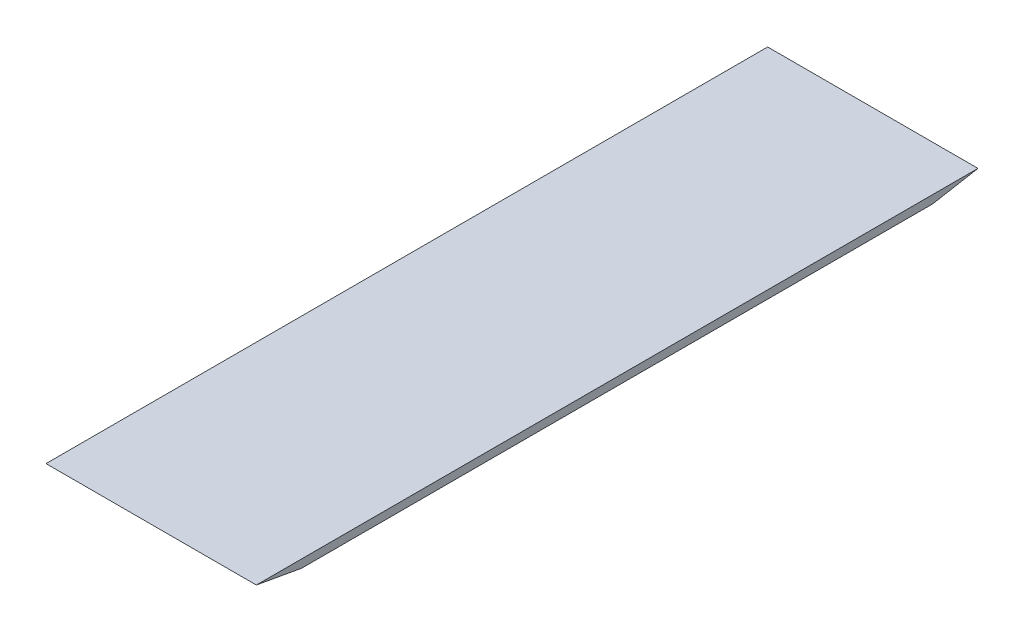
SolidWorks part; units mm, degrees
ref_plane "Front Plane" through (0, 0, 0) normal (0, 0, 1) x (1, 0, 0)
ref_plane "Top Plane" through (0, 0, 0) normal (0, 1, 0) x (1, 0, 0)
ref_plane "Right Plane" through (0, 0, 0) normal (1, 0, 0) x (0, 0, -1)
sketch "Sketch1" plane through (0, 0, 0) normal (1, 0, 0) x (0, 0, -1)
  line L0 (0, 0) -> (446, 0)
  line L1 (446, 0) -> (418, -5)
  line L2 (418, -5) -> (28, -5)
  line L3 (28, -5) -> (0, 0)
  dimension "D1" = 390
  dimension "D2" = 28
  dimension "D3" = 28
  dimension "D4" = 5
extrude "Boss-Extrude1" add sketch "Sketch1" along normal blind 130 contours L2 L3 L0 L1
